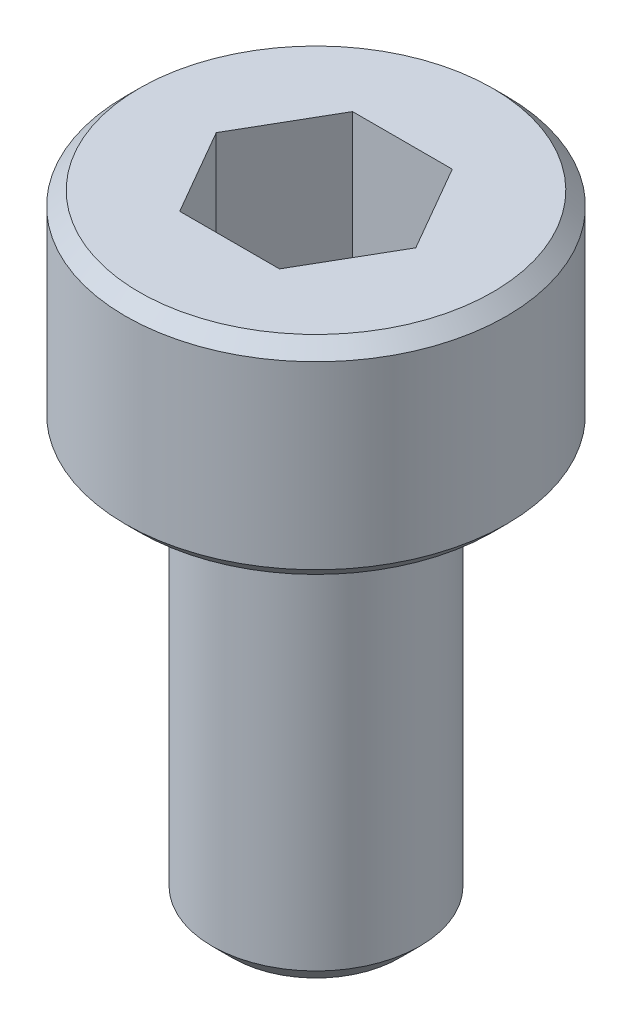
SolidWorks part; units mm, degrees
material "AISI 304"
ref_plane "前视基准面" through (0, 0, 0) normal (0, 0, 1) x (1, 0, 0)
ref_plane "上视基准面" through (0, 0, 0) normal (0, 1, 0) x (1, 0, 0)
ref_plane "右视基准面" through (0, 0, 0) normal (1, 0, 0) x (0, 0, -1)
sketch "草图1" plane through (0, 0, 0) normal (0, 0, 1) x (1, 0, 0)
  line L0 (1.5, 0) -> (2.75, 0)
  line L1 (2.75, 0) -> (2.75, 3)
  line L2 (2.75, 3) -> (0, 3)
  line L3 (0, 3) -> (0, 0)
  line L4 (1.5, 0) -> (1.5, -6)
  line L5 (1.5, -6) -> (0, -6)
  line L6 (0, -6) -> (0, 0)
  dimension "D1" = 3
  dimension "D2" = 2.75
  dimension "D3" = 1.5
  dimension "D4" = 6
  dimension "D5" = 2.75
revolve "旋转1" add sketch "草图1" angle 360 about L3
chamfer "倒角1" distance 0.2 angle 45 2 edges at (0, 0, 2.75) (0, 3, 2.75)
chamfer "倒角2" distance 0.3 angle 45 1 edges at (0, -6, 1.5)
sketch "草图2" plane through (0, 3, 0) normal (0, 1, 0) x (1, 0, 0)
  line L0 (-0.72, 1.2471) -> (0.72, 1.2471)
  line L1 (0.72, 1.2471) -> (1.44, 0)
  line L2 (1.44, 0) -> (0.72, -1.2471)
  line L3 (0.72, -1.2471) -> (-0.72, -1.2471)
  line L4 (-0.72, -1.2471) -> (-1.44, 0)
  line L5 (-1.44, 0) -> (-0.72, 1.2471)
extrude "切除-拉伸1" cut sketch "草图2" against normal blind 2.5
